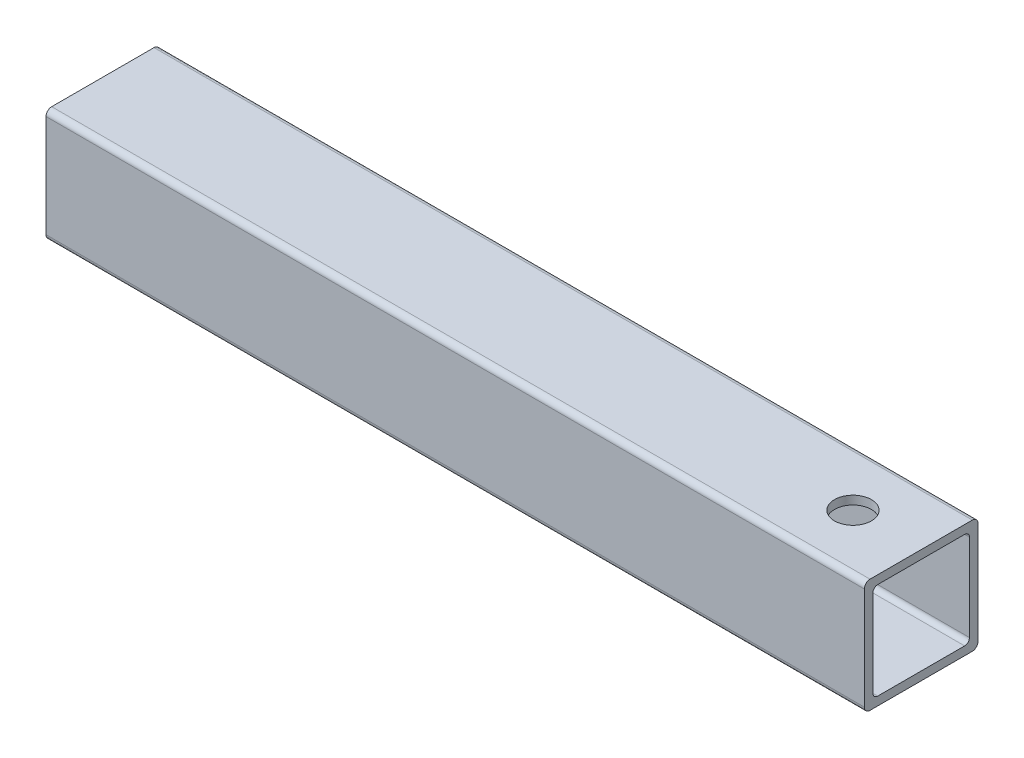
SolidWorks part; units mm, degrees
ref_plane "Front Plane" through (0, 0, 0) normal (0, 0, 1) x (1, 0, 0)
ref_plane "Top Plane" through (0, 0, 0) normal (0, 1, 0) x (1, 0, 0)
ref_plane "Right Plane" through (0, 0, 0) normal (1, 0, 0) x (0, 0, -1)
sketch "Sketch2" plane through (0, 0, 0) normal (0, 0, 1) x (1, 0, 0)
  line L0 (0, 0) -> (457.2, 0)
  dimension "D1" = 457.2
other "Square tube 2.5X2.5X.188 A500(1)"
ref_plane "Plane1" through (0, 0, 0) normal (1, 0, 0) x (0, 1, 0)
sketch "Sketch1" plane through (0, 0, 0) normal (1, 0, 0) x (0, 1, 0)
  line L0 (-26.9748, 0) -> (-31.75, 0) construction
  line L1 (28.575, -31.75) -> (-28.575, -31.75)
  line L2 (31.75, -28.575) -> (31.75, 28.575)
  line L3 (28.575, 31.75) -> (-28.575, 31.75)
  line L4 (-31.75, -28.575) -> (-31.75, 28.575)
  line L5 (31.75, -31.75) -> (-31.75, 31.75) construction
  line L6 (31.75, 31.75) -> (-31.75, -31.75) construction
  line L7 (24.2773, 26.9748) -> (-24.2773, 26.9748)
  line L8 (26.9748, 24.2773) -> (26.9748, -24.2773)
  line L9 (24.2773, -26.9748) -> (-24.2773, -26.9748)
  line L10 (-26.9748, 24.2773) -> (-26.9748, -24.2773)
  line L11 (26.9748, 26.9748) -> (-26.9748, -26.9748) construction
  line L12 (26.9748, -26.9748) -> (-26.9748, 26.9748) construction
  line L13 (0, -26.9748) -> (0, -31.75) construction
  line L14 (26.9748, -24.2773) -> (26.9748, -31.75) construction
  line L15 (26.9748, 0) -> (31.75, 0) construction
  line L16 (26.9748, -31.75) -> (31.75, -31.75) construction
  arc A0 (-24.2773, -26.9748) -> (-26.9748, -24.2773) centre (-24.2773, -24.2773) cw
  arc A1 (26.9748, -24.2773) -> (24.2773, -26.9748) centre (24.2773, -24.2773) cw
  arc A2 (24.2773, 26.9748) -> (26.9748, 24.2773) centre (24.2773, 24.2773) cw
  arc A3 (-24.2773, 26.9748) -> (-26.9748, 24.2773) centre (-24.2773, 24.2773) ccw
  arc A4 (28.575, -31.75) -> (31.75, -28.575) centre (28.575, -28.575) ccw
  arc A5 (31.75, 28.575) -> (28.575, 31.75) centre (28.575, 28.575) ccw
  arc A6 (-28.575, 31.75) -> (-31.75, 28.575) centre (-28.575, 28.575) ccw
  arc A7 (-28.575, -31.75) -> (-31.75, -28.575) centre (-28.575, -28.575) cw
  point P0 (0, 0)
  point P6 (0, 0)
  point P44 (0, 0)
  dimension "D2" = 2.6975
  dimension "D3" = 3.175
  dimension "D1" = 53.9496
  dimension "Outside Width" = 63.5
  dimension "Ouside Height" = 63.5
  dimension "Wall Thickness" = 4.7752
sketch "Sketch3" plane through (0, 31.75, 0) normal (0, 1, 0) x (1, 0, 0)
  line L0 (0, 0) -> (457.2, 0) construction
  line L1 (457.2, 28.575) -> (457.2, -28.575) construction
  circle A0 centre (419.1, 0) radius 10.3251
  dimension "D1" = 20.6502
  dimension "D2" = 38.1
extrude "Cut-Extrude1" cut sketch "Sketch3" against normal up to surface (4.7752 mm away) contours A0 up to face at (228.6, 26.9748, 0)
equation "\"D3@Sketch1\"=\"Outside Width@Sketch1\"*.05"
equation "\"D2@Sketch1\"=\"D1@Sketch1\"*.05"
